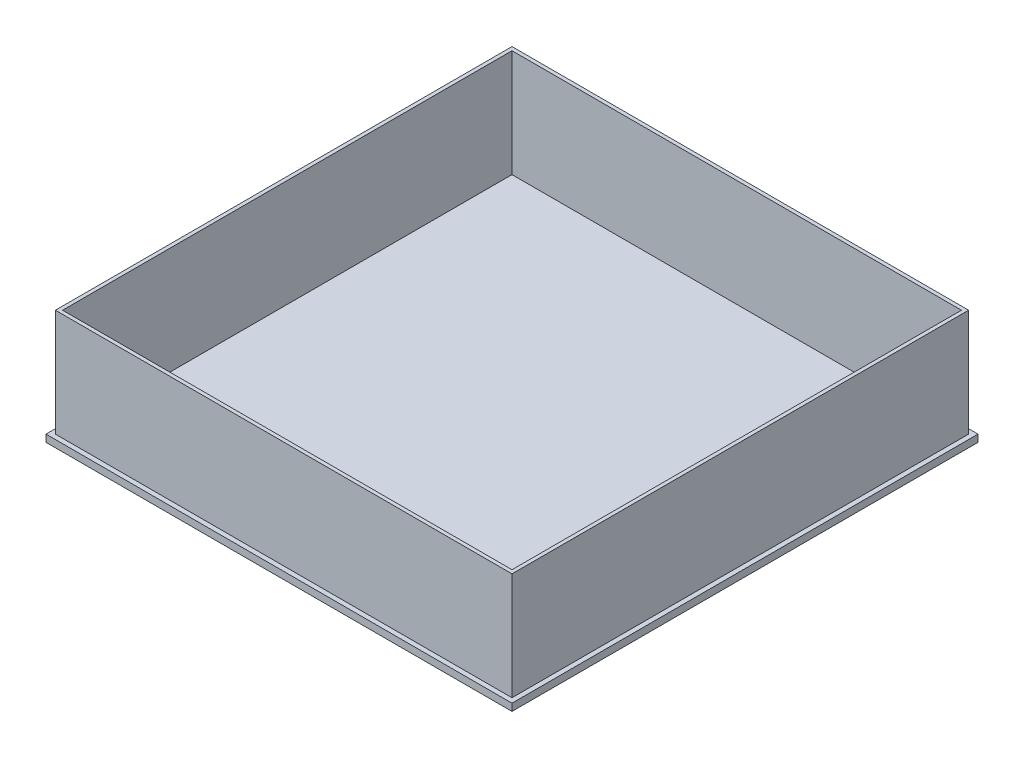
SolidWorks part; units mm, degrees
ref_plane "前视" through (0, 0, 0) normal (0, 0, 1) x (1, 0, 0)
ref_plane "上视" through (0, 0, 0) normal (0, 1, 0) x (1, 0, 0)
ref_plane "右视" through (0, 0, 0) normal (1, 0, 0) x (0, 0, -1)
sketch "草图2" plane through (0, 0, 0) normal (0, 1, 0) x (1, 0, 0)
  line L1 (65.1359, -65.1359) -> (-65.1359, -65.1359)
  line L2 (65.1359, -65.1359) -> (65.1359, 65.1359)
  line L3 (65.1359, 65.1359) -> (-65.1359, 65.1359)
  line L4 (-65.1359, -65.1359) -> (-65.1359, 65.1359)
  line L5 (65.1359, -65.1359) -> (-65.1359, 65.1359) construction
  line L6 (65.1359, 65.1359) -> (-65.1359, -65.1359) construction
  point P0 (0, 0)
extrude "凸台-拉伸1" add sketch "草图2" along normal blind 2
sketch "草图3" plane through (0, 2, 0) normal (0, 1, 0) x (1, 0, 0)
  line L0 (-62.8242, 62.8242) -> (62.8242, 62.8242)
  line L1 (-63.8242, -63.8242) -> (63.8242, -63.8242)
  line L2 (-63.8242, -63.8242) -> (-63.8242, 63.8242)
  line L3 (-63.8242, 63.8242) -> (63.8242, 63.8242)
  line L4 (63.8242, -63.8242) -> (63.8242, 63.8242)
  line L5 (-63.8242, -63.8242) -> (63.8242, 63.8242) construction
  line L6 (-63.8242, 63.8242) -> (63.8242, -63.8242) construction
  line L7 (62.8242, -62.8242) -> (62.8242, 62.8242)
  line L8 (-62.8242, -62.8242) -> (62.8242, -62.8242)
  line L9 (-62.8242, -62.8242) -> (-62.8242, 62.8242)
  point P0 (0, 0)
  dimension "D1" = 1
extrude "凸台-拉伸2" add sketch "草图3" along normal blind 30
